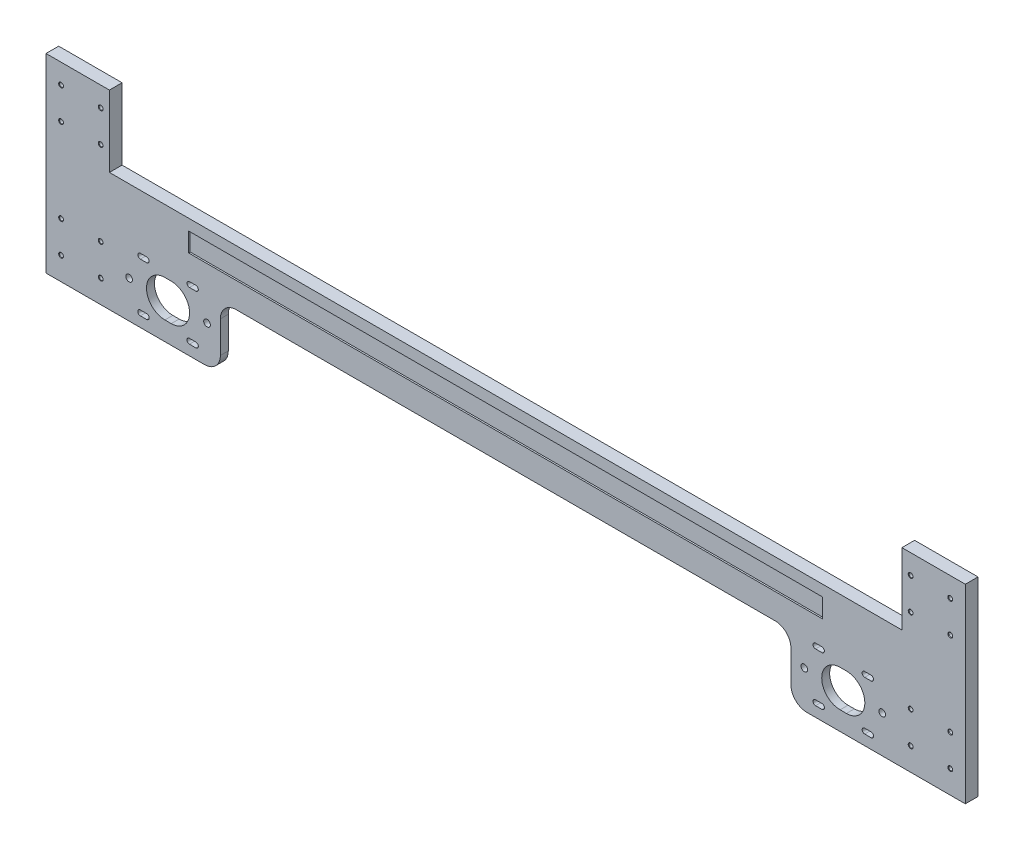
SolidWorks part; units mm, degrees
ref_plane "Front Plane" through (0, 0, 0) normal (0, 0, 1) x (1, 0, 0)
ref_plane "Top Plane" through (0, 0, 0) normal (0, 1, 0) x (1, 0, 0)
ref_plane "Right Plane" through (0, 0, 0) normal (1, 0, 0) x (0, 0, -1)
sketch "Sketch1" plane through (0, 0, 0) normal (0, 0, 1) x (1, 0, 0)
  line L0 (-230.5, -24.2798) -> (-226.5, -24.2798)
  line L1 (-240, -33.8798) -> (-200, -33.8798)
  line L2 (-250, -23.8798) -> (-250, 36.1202)
  line L4 (250, -33.8798) -> (250, 36.1202)
  line L6 (-150, 6.1202) -> (150, 6.1202)
  line L7 (240, -33.8798) -> (200, -33.8798)
  line L8 (170, 6.1202) -> (150, 6.1202)
  line L9 (-250, -23.8798) -> (-250, -33.8798)
  line L10 (-250, -33.8798) -> (-240, -33.8798)
  line L11 (-230.5, -27.4798) -> (-226.5, -27.4798)
  line L12 (-211, 1.2202) -> (-215, 1.2202)
  line L13 (-211, -21.9798) -> (-215, -21.9798)
  line L14 (-195.5, -27.4798) -> (-199.5, -27.4798)
  line L15 (-195.5, 6.7202) -> (-199.5, 6.7202)
  line L16 (-195.5, 3.5202) -> (-199.5, 3.5202)
  line L17 (-213, -22.3798) -> (-213, 7.8028) construction
  line L18 (-195.5, -24.2798) -> (-199.5, -24.2798)
  line L19 (-230.5, 3.5202) -> (-226.5, 3.5202)
  line L20 (-230.5, 6.7202) -> (-226.5, 6.7202)
  line L21 (-195.5, 6.7202) -> (-199.5, 6.7202)
  line L22 (-195.5, 3.5202) -> (-199.5, 3.5202)
  line L23 (-230.5, -24.2798) -> (-226.5, -24.2798)
  line L24 (-230.5, 3.5202) -> (-226.5, 3.5202)
  line L25 (-230.5, 6.7202) -> (-226.5, 6.7202)
  line L26 (-230.5, -27.4798) -> (-226.5, -27.4798)
  line L27 (-195.5, -27.4798) -> (-199.5, -27.4798)
  line L28 (213, -22.3798) -> (213, 7.8028) construction
  line L29 (-195.5, -24.2798) -> (-199.5, -24.2798)
  line L30 (0, 0) -> (0, 53.8105) construction
  line L31 (195.5, -24.2798) -> (199.5, -24.2798)
  line L32 (195.5, -27.4798) -> (199.5, -27.4798)
  line L33 (230.5, -27.4798) -> (226.5, -27.4798)
  line L34 (230.5, 6.7202) -> (226.5, 6.7202)
  line L35 (230.5, 3.5202) -> (226.5, 3.5202)
  line L36 (230.5, -24.2798) -> (226.5, -24.2798)
  line L37 (195.5, 3.5202) -> (199.5, 3.5202)
  line L38 (195.5, 6.7202) -> (199.5, 6.7202)
  line L39 (230.5, 6.7202) -> (226.5, 6.7202)
  line L40 (230.5, 3.5202) -> (226.5, 3.5202)
  line L41 (195.5, -24.2798) -> (199.5, -24.2798)
  line L42 (195.5, 3.5202) -> (199.5, 3.5202)
  line L43 (195.5, 6.7202) -> (199.5, 6.7202)
  line L44 (195.5, -27.4798) -> (199.5, -27.4798)
  line L45 (211, -21.9798) -> (215, -21.9798)
  line L46 (211, 1.2202) -> (215, 1.2202)
  line L47 (230.5, -27.4798) -> (226.5, -27.4798)
  line L48 (230.5, -24.2798) -> (226.5, -24.2798)
  line L49 (240, -33.8798) -> (250, -33.8798)
  line L50 (150, 6.1202) -> (170, 6.1202)
  line L51 (-170, 6.1202) -> (-150, 6.1202)
  line L52 (-150, 6.1202) -> (-149.7779, 5.8283)
  line L53 (-200, -33.8798) -> (-190, -33.8798)
  line L54 (-180, -23.8798) -> (-180, -3.8798)
  line L55 (200, -33.8798) -> (190, -33.8798)
  line L56 (180, -23.8798) -> (180, -3.8798)
  line L58 (-250, 36.1202) -> (-250, 41.1202)
  line L59 (-250, 41.1202) -> (250, 41.1202)
  line L60 (250, 36.1202) -> (250, 41.1202)
  arc A0 (-211, -21.9798) -> (-211, 1.2202) centre (-211, -10.3798) ccw
  arc A1 (-226.5, -27.4798) -> (-226.5, -24.2798) centre (-226.5, -25.8798) ccw
  arc A2 (-230.5, -24.2798) -> (-230.5, -27.4798) centre (-230.5, -25.8798) ccw
  arc A3 (-215, 1.2202) -> (-215, -21.9798) centre (-215, -10.3798) ccw
  arc A4 (-195.5, 3.5202) -> (-195.5, 6.7202) centre (-195.5, 5.1202) ccw
  arc A5 (-199.5, 6.7202) -> (-199.5, 3.5202) centre (-199.5, 5.1202) ccw
  arc A6 (-195.5, -24.2798) -> (-195.5, -27.4798) centre (-195.5, -25.8798) cw
  arc A7 (-199.5, -27.4798) -> (-199.5, -24.2798) centre (-199.5, -25.8798) cw
  arc A8 (-226.5, 6.7202) -> (-226.5, 3.5202) centre (-226.5, 5.1202) cw
  arc A9 (-230.5, 3.5202) -> (-230.5, 6.7202) centre (-230.5, 5.1202) cw
  arc A10 (-195.5, 3.5202) -> (-195.5, 6.7202) centre (-195.5, 5.1202) ccw
  arc A11 (-199.5, 6.7202) -> (-199.5, 3.5202) centre (-199.5, 5.1202) ccw
  arc A12 (-226.5, -27.4798) -> (-226.5, -24.2798) centre (-226.5, -25.8798) ccw
  arc A13 (-230.5, -24.2798) -> (-230.5, -27.4798) centre (-230.5, -25.8798) ccw
  arc A14 (-226.5, 6.7202) -> (-226.5, 3.5202) centre (-226.5, 5.1202) cw
  arc A15 (-230.5, 3.5202) -> (-230.5, 6.7202) centre (-230.5, 5.1202) cw
  arc A16 (-211, 1.2202) -> (-211, -21.9798) centre (-211, -10.3798) cw
  arc A17 (-195.5, -24.2798) -> (-195.5, -27.4798) centre (-195.5, -25.8798) cw
  arc A18 (-199.5, -27.4798) -> (-199.5, -24.2798) centre (-199.5, -25.8798) cw
  arc A19 (-215, -21.9798) -> (-215, 1.2202) centre (-215, -10.3798) cw
  arc A20 (215, -21.9798) -> (215, 1.2202) centre (215, -10.3798) ccw
  arc A21 (199.5, -27.4798) -> (199.5, -24.2798) centre (199.5, -25.8798) ccw
  arc A22 (195.5, -24.2798) -> (195.5, -27.4798) centre (195.5, -25.8798) ccw
  arc A23 (211, 1.2202) -> (211, -21.9798) centre (211, -10.3798) ccw
  arc A24 (230.5, 3.5202) -> (230.5, 6.7202) centre (230.5, 5.1202) ccw
  arc A25 (226.5, 6.7202) -> (226.5, 3.5202) centre (226.5, 5.1202) ccw
  arc A26 (230.5, -24.2798) -> (230.5, -27.4798) centre (230.5, -25.8798) cw
  arc A27 (226.5, -27.4798) -> (226.5, -24.2798) centre (226.5, -25.8798) cw
  arc A28 (199.5, 6.7202) -> (199.5, 3.5202) centre (199.5, 5.1202) cw
  arc A29 (195.5, 3.5202) -> (195.5, 6.7202) centre (195.5, 5.1202) cw
  arc A30 (230.5, 3.5202) -> (230.5, 6.7202) centre (230.5, 5.1202) ccw
  arc A31 (226.5, 6.7202) -> (226.5, 3.5202) centre (226.5, 5.1202) ccw
  arc A32 (199.5, -27.4798) -> (199.5, -24.2798) centre (199.5, -25.8798) ccw
  arc A33 (195.5, -24.2798) -> (195.5, -27.4798) centre (195.5, -25.8798) ccw
  arc A34 (199.5, 6.7202) -> (199.5, 3.5202) centre (199.5, 5.1202) cw
  arc A35 (195.5, 3.5202) -> (195.5, 6.7202) centre (195.5, 5.1202) cw
  arc A36 (215, 1.2202) -> (215, -21.9798) centre (215, -10.3798) cw
  arc A37 (230.5, -24.2798) -> (230.5, -27.4798) centre (230.5, -25.8798) cw
  arc A38 (226.5, -27.4798) -> (226.5, -24.2798) centre (226.5, -25.8798) cw
  arc A39 (211, -21.9798) -> (211, 1.2202) centre (211, -10.3798) cw
  arc A42 (-180, -3.8798) -> (-170, 6.1202) centre (-170, -3.8798) cw
  arc A43 (-180, -23.8798) -> (-190, -33.8798) centre (-190, -23.8798) cw
  arc A44 (180, -3.8798) -> (170, 6.1202) centre (170, -3.8798) ccw
  arc A45 (180, -23.8798) -> (190, -33.8798) centre (190, -23.8798) ccw
  point P29 (-213, -10.3798)
  point P82 (0, 6.1202)
  point P89 (190.4675, 6.1202)
  point P92 (-180, -33.8798)
  dimension "D6" = 3.2
  dimension "D7" = 23.2
  dimension "D8" = 4
  dimension "D5" = 10
  dimension "D2" = 5
  dimension "D14" = 10
  dimension "D1" = 500
  dimension "D3" = 23.5
  dimension "D4" = 23.5
  dimension "D9" = 4
  dimension "D10" = 20
  dimension "D12" = 2
  dimension "D13" = 211
  dimension "D15" = 60
  dimension "D16" = 250
  dimension "D17" = 15.5
extrude "Boss-Extrude1" add sketch "Sketch1" along normal blind 8
sketch "Sketch4" plane through (0, 0, 8) normal (0, 0, 1) x (1, 0, 0)
  line L0 (211, -21.9798) -> (215, -21.9798) construction
  line L1 (211, 1.2202) -> (215, 1.2202) construction
  line L2 (-211, -21.9798) -> (-215, -21.9798) construction
  line L3 (-211, 1.2202) -> (-215, 1.2202) construction
  line L4 (211, -21.9798) -> (215, -21.9798)
  line L5 (211, 1.2202) -> (215, 1.2202)
  line L6 (-211, -21.9798) -> (-215, -21.9798)
  line L7 (-211, 1.2202) -> (-215, 1.2202)
  arc A0 (215, -21.9798) -> (215, 1.2202) centre (215, -10.3798) ccw construction
  arc A1 (211, 1.2202) -> (211, -21.9798) centre (211, -10.3798) ccw construction
  arc A2 (-215, 1.2202) -> (-215, -21.9798) centre (-215, -10.3798) ccw construction
  arc A3 (-211, -21.9798) -> (-211, 1.2202) centre (-211, -10.3798) ccw construction
  arc A4 (215, -21.9798) -> (215, 1.2202) centre (215, -10.3798) ccw
  arc A5 (211, 1.2202) -> (211, -21.9798) centre (211, -10.3798) ccw
  arc A6 (-215, 1.2202) -> (-215, -21.9798) centre (-215, -10.3798) ccw
  arc A7 (-211, -21.9798) -> (-211, 1.2202) centre (-211, -10.3798) ccw
sketch "Sketch5" plane through (-195.8798, 36.1202, 8) normal (0, 0, -1) x (0, -1, 0)
  line L1 (70, 94.1202) -> (-50, 94.1202)
  line L2 (70, 94.1202) -> (70, 54.1202)
  line L3 (70, 54.1202) -> (-50, 54.1202)
  line L4 (-50, 94.1202) -> (-50, 54.1202)
  point P6 (-17.5, 59.6202)
  point P8 (-37.5, 59.6202)
  point P9 (-37.5, 84.6202)
  point P10 (-17.5, 84.6202)
  dimension "D1" = 120
  dimension "D2" = 40
  dimension "D3" = 25
  dimension "D4" = 20
  dimension "D5" = 12.5
  dimension "D12" = 20
extrude "Boss-Extrude4" add sketch "Sketch5" along normal blind 8
sketch "Sketch11" plane through (0, 0, 8) normal (0, 0, 1) x (0, -1, 0)
  point P0 (-53.6202, -280.5)
  point P1 (-53.6202, -255.5)
  point P5 (-73.6202, -255.5)
  point P11 (-73.6202, -280.5)
  dimension "D1" = 25
  dimension "D2" = 25
  dimension "D3" = 20
hole_wizard "M3 Tapped Hole2" positions "3DSketch5" profile "Sketch13" tap size "M3" standard "ISO" end condition through all
sketch3d "3DSketch5"
  point P0 (-280.5, 53.6202, 8)
  point P6 (-255.5, 73.6202, 8)
  point P9 (-255.5, 53.6202, 8)
  point P13 (-280.5, 73.6202, 8)
cosmetic thread "Hole Thread1" parameters "D2"=3
cosmetic thread "Hole Thread2" parameters "D2"=3
cosmetic thread "Hole Thread4" parameters "D2"=3
cosmetic thread "Hole Thread5" parameters "D2"=3
sketch "Sketch13" plane through (-280.5, 53.6202, 8) normal (1, 0, 0) x (0, -1, 0)
  line L0 (0, 0) -> (0, 8)
  line L1 (0, 8) -> (1.25, 8)
  line L2 (1.25, 8) -> (1.25, 0.275)
  line L3 (1.25, 0.275) -> (1.525, 0)
  line L5 (1.525, 0) -> (0, 0)
  line L6 (-1.25, 0.275) -> (-1.525, 0) construction
  line L11 (0, -6.35) -> (0, 107.95) construction
  dimension "Thru Tap Drill Dia." = 2.5
  dimension "Thru Tap Drill Depth" = 8
  dimension "Near C'Sink Dia." = 3.05
  dimension "Near C'Sink Angle" = 90
mirror "Mirror1" about plane through (0, 0, 0) normal (1, 0, 0) of "Boss-Extrude4", "M3 Tapped Hole2"
sketch "Sketch24" plane through (0, 0, 8) normal (0, 0, 1) x (1, 0, 0)
  line L1 (-200, 34.1202) -> (200, 34.1202)
  line L2 (-200, 34.1202) -> (-200, 22.1202)
  line L3 (-200, 22.1202) -> (200, 22.1202)
  line L4 (200, 34.1202) -> (200, 22.1202)
  point P7 (-200, 28.1202)
  dimension "D1" = 400
  dimension "D2" = 12
extrude "Cut-Extrude4" cut sketch "Sketch24" against normal blind 1
sketch "Sketch25" plane through (0, 0, 0) normal (0, 0, 1) x (1, 0, 0)
  line L0 (-213, 1.2202) -> (-213, -41.5295) construction
  line L1 (0, 0) -> (0, 61.2251) construction
  line L2 (-211, 1.2202) -> (-215, 1.2202) construction
  line L3 (213, 1.2202) -> (213, -28.4754) construction
  line L4 (211, 1.2202) -> (215, 1.2202) construction
  arc A0 (-215, 1.2202) -> (-215, -21.9798) centre (-215, -10.3798) ccw construction
  arc A1 (-215, 1.2202) -> (-215, -21.9798) centre (-215, -10.3798) ccw
  circle A2 centre (-237.58, -10.3798) radius 2.5
  circle A3 centre (237.58, -10.3798) radius 2.5
  circle A4 centre (-188.42, -10.3798) radius 2.5
  circle A5 centre (188.42, -10.3798) radius 2.5
  dimension "D1" = 5
hole_wizard "M5 Tapped Hole3" positions "Sketch29" profile "Sketch30" tap size "M5" standard "ISO" end condition up to next
sketch "Sketch29" plane through (0, 0, 0) normal (0, 0, -1) x (-1, 0, 0)
  point P0 (237.58, -10.3798)
  point P3 (188.42, -10.3798)
  point P6 (-188.42, -10.3798)
  point P9 (-237.58, -10.3798)
sketch "Sketch30" plane through (-237.58, -10.3798, 0) normal (1, 0, 0) x (0, 1, 0)
  line L0 (0, 0) -> (0, 8)
  line L1 (0, 8) -> (2.1, 8)
  line L2 (2.1, 8) -> (2.1, 0.425)
  line L3 (2.1, 0.425) -> (2.525, 0)
  line L5 (2.525, 0) -> (0, 0)
  line L6 (-2.1, 0.425) -> (-2.525, 0) construction
  line L11 (0, -6.35) -> (0, 107.95) construction
  dimension "Thru Tap Drill Dia." = 4.2
  dimension "Thru Tap Drill Depth" = 8
  dimension "Near C'Sink Dia." = 5.05
  dimension "Near C'Sink Angle" = 90
cosmetic thread "Hole Thread6" parameters "D2"=5
cosmetic thread "Hole Thread7" parameters "D2"=5
cosmetic thread "Hole Thread8" parameters "D2"=5
cosmetic thread "Hole Thread9" parameters "D2"=5
sketch "Sketch26" plane through (0, 0, 8) normal (0, 0, 1) x (1, 0, 0)
  line L0 (-280.9751, 38.6202) -> (-255.5, 38.6202)
  circle A1 centre (-255.5, 53.6202) radius 1.525 construction
  circle A3 centre (-255.5, 53.6202) radius 1.525
  dimension "D1" = 15
ref_plane "Plane1" through (0, 38.6202, 0) normal (0, -1, 0) x (1, 0, 0)
ref_plane "Plane3" through (0, 27.1202, 0) normal (0, -1, 0) x (1, 0, 0)
mirror "Mirror2" about plane through (0, 27.1202, 0) normal (0, -1, 0) of "M3 Tapped Hole2"
mirror "Mirror3" about plane through (0, 0, 0) normal (1, 0, 0) of "Mirror2"
sketch "Sketch27" plane through (0, -33.8798, 0) normal (0, -1, 0) x (1, 0, 0)
  line L1 (170, 8) -> (170, 0) construction
  line L2 (244.08, -7.6909) -> (166, -7.6909)
  line L3 (244.08, -7.6909) -> (244.08, 3)
  line L4 (244.08, -7.6909) -> (244.08, 3)
  line L6 (244.08, 3) -> (166, 3)
  line L7 (166, -7.6909) -> (166, 3)
  line L8 (290, 0) -> (190, 0) construction
  line M3 (190, 0) -> (290, 0)
  line M9 (190, 8) -> (190, 0)
  dimension "D2" = 4
  dimension "D3" = 3
extrude "Cut-Extrude6" cut sketch "Sketch27" against normal blind 50 contours L3 L6 M9 M3 | L7 L2 L3 L6 M3 M9
mirror "Mirror4" about plane through (0, 0, 0) normal (1, 0, 0) of "Cut-Extrude6"
